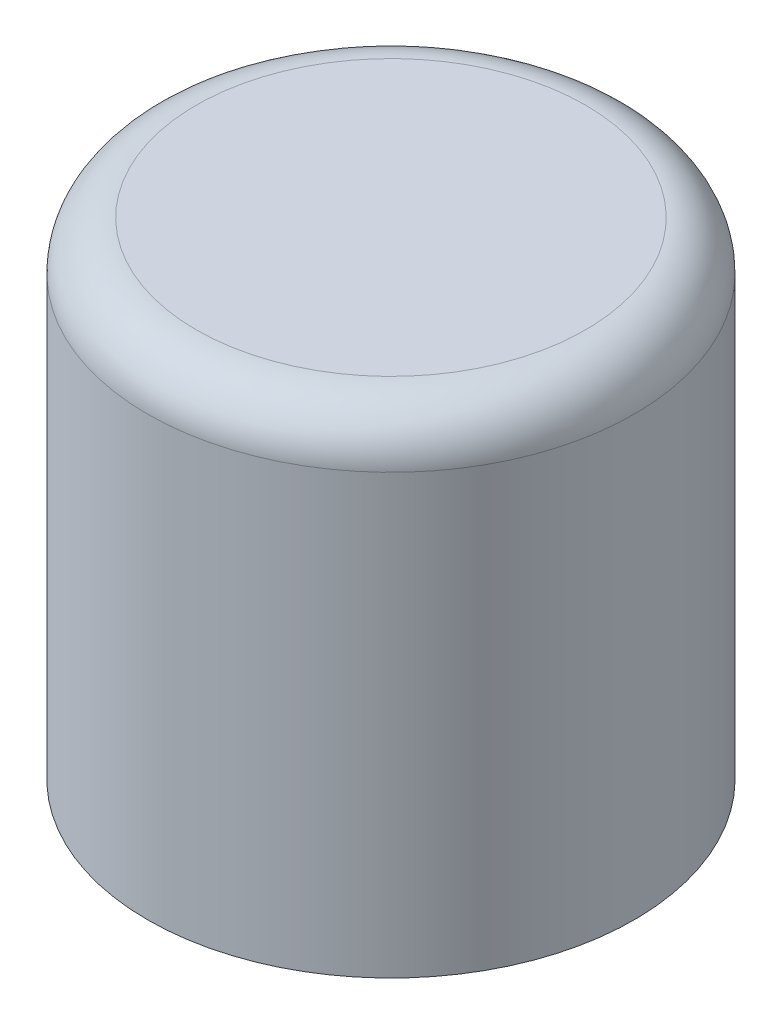
SolidWorks part; units mm, degrees
ref_plane "Front Plane" through (0, 0, 0) normal (0, 0, 1) x (1, 0, 0)
ref_plane "Top Plane" through (0, 0, 0) normal (0, 1, 0) x (1, 0, 0)
ref_plane "Right Plane" through (0, 0, 0) normal (1, 0, 0) x (0, 0, -1)
sketch "Sketch1" plane through (0, 0, 0) normal (0, 1, 0) x (1, 0, 0)
  circle A0 centre (0, 0) radius 10.16
  dimension "D1" = 20.32
extrude "Boss-Extrude1" add sketch "Sketch1" along normal blind 20.32
fillet "Fillet1" radius 2.032 1 edges at (0, 20.32, 10.16)
